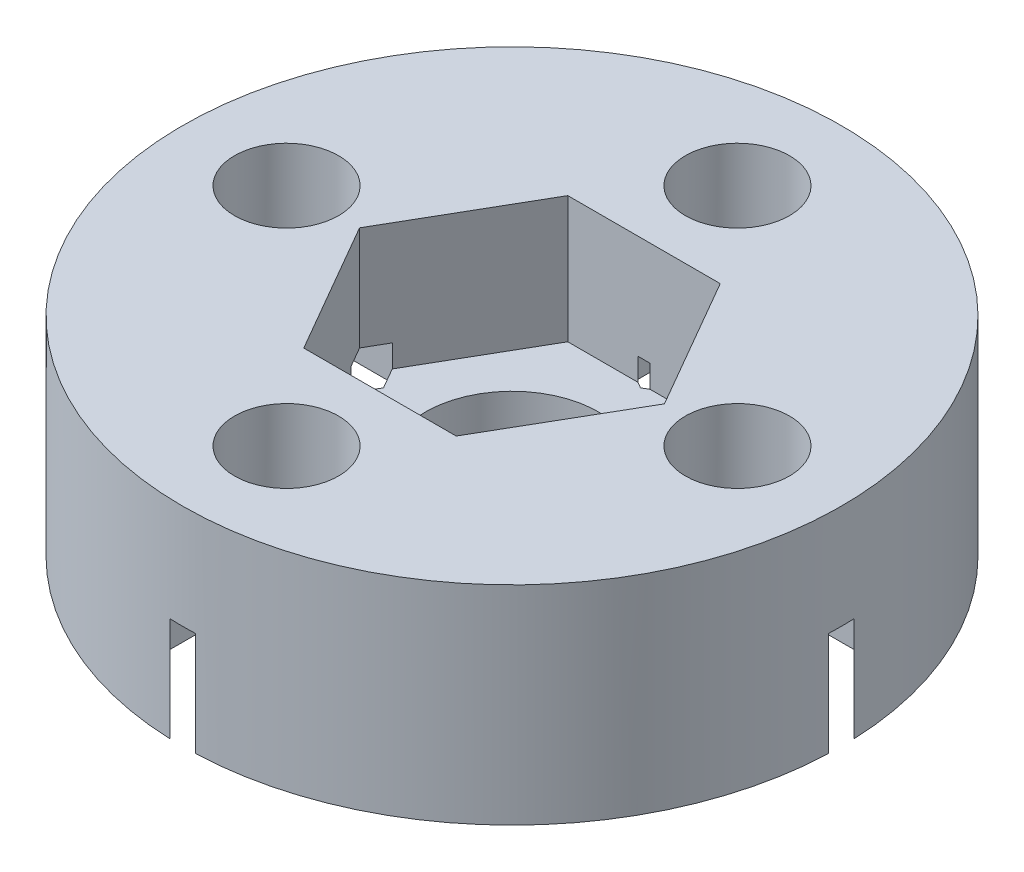
SolidWorks part; units mm, degrees
ref_plane "Front Plane" through (0, 0, 0) normal (0, 0, 1) x (1, 0, 0)
ref_plane "Top Plane" through (0, 0, 0) normal (0, 1, 0) x (1, 0, 0)
ref_plane "Right Plane" through (0, 0, 0) normal (1, 0, 0) x (0, 0, -1)
sketch "Sketch2" plane through (0, 0, 0) normal (0, 1, 0) x (1, 0, 0)
  circle A0 centre (0, 0) radius 9.5
  dimension "D1" = 19
extrude "Boss-Extrude1" add sketch "Sketch2" along normal blind 6
sketch "Sketch3" plane through (0, 6, 0) normal (0, 1, 0) x (1, 0, 0)
  line L1 (2.1975, -3.8062) -> (4.395, 0)
  line L2 (4.395, 0) -> (2.1975, 3.8062)
  line L3 (2.1975, 3.8062) -> (-2.1975, 3.8062)
  line L4 (-2.1975, 3.8062) -> (-4.395, 0)
  line L5 (-4.395, 0) -> (-2.1975, -3.8062)
  line L6 (-2.1975, -3.8062) -> (2.1975, -3.8062)
  circle A0 centre (0, 0) radius 3.8062 construction
  dimension "D1" = 8.79
extrude "Cut-Extrude1" cut sketch "Sketch3" against normal blind 3.65
sketch "Sketch4" plane through (0, 2.35, 0) normal (0, 1, 0) x (1, 0, 0)
  circle A0 centre (0, 0) radius 2.5
  dimension "D1" = 5
extrude "Cut-Extrude2" cut sketch "Sketch4" against normal through all
sketch "Sketch5" plane through (0, 6, 0) normal (0, 1, 0) x (1, 0, 0)
  circle A0 centre (6.5, 0) radius 1.5
  circle A1 centre (0, 0) radius 2.5 construction
  circle A2 centre (0, -6.5) radius 1.5
  circle A3 centre (-6.5, 0) radius 1.5
  circle A4 centre (0, 6.5) radius 1.5
  dimension "D1" = 3
  dimension "D2" = 6.5
  dimension "D3" = 4
sketch "Sketch6" plane through (0, 0, 0) normal (0, -1, 0) x (1, 0, 0)
  line L0 (-2.5981, -8.2049) -> (0, -9.7049)
  line L17 (8.2049, -2.5981) -> (9.7049, 0)
  line L18 (9.7049, 0) -> (8.2049, 2.5981)
  line L19 (8.2049, 2.5981) -> (5.2049, 2.5981)
  line L20 (5.2049, 2.5981) -> (3.7049, 0)
  line L21 (3.7049, 0) -> (5.2049, -2.5981)
  line L22 (5.2049, -2.5981) -> (8.2049, -2.5981)
  line L23 (0, -9.7049) -> (2.5981, -8.2049)
  line L24 (2.5981, -8.2049) -> (2.5981, -5.2049)
  line L25 (2.5981, -5.2049) -> (0, -3.7049)
  line L26 (0, -3.7049) -> (-2.5981, -5.2049)
  line L27 (-2.5981, -5.2049) -> (-2.5981, -8.2049)
  line L28 (-8.2049, 2.5981) -> (-9.7049, 0)
  line L29 (-9.7049, 0) -> (-8.2049, -2.5981)
  line L30 (-8.2049, -2.5981) -> (-5.2049, -2.5981)
  line L31 (-5.2049, -2.5981) -> (-3.7049, 0)
  line L32 (-3.7049, 0) -> (-5.2049, 2.5981)
  line L33 (-5.2049, 2.5981) -> (-8.2049, 2.5981)
  line L34 (2.5981, 8.2049) -> (0, 9.7049)
  line L35 (0, 9.7049) -> (-2.5981, 8.2049)
  line L36 (-2.5981, 8.2049) -> (-2.5981, 5.2049)
  line L37 (-2.5981, 5.2049) -> (0, 3.7049)
  line L38 (0, 3.7049) -> (2.5981, 5.2049)
  line L39 (2.5981, 5.2049) -> (2.5981, 8.2049)
  circle A0 centre (6.7049, 0) radius 2.5981 construction
  dimension "D1" = 6
  dimension "D2" = 4
extrude "Cut-Extrude4" cut sketch "Sketch6" against normal blind 3
extrude "Cut-Extrude5" cut sketch "Sketch5" against normal through all
